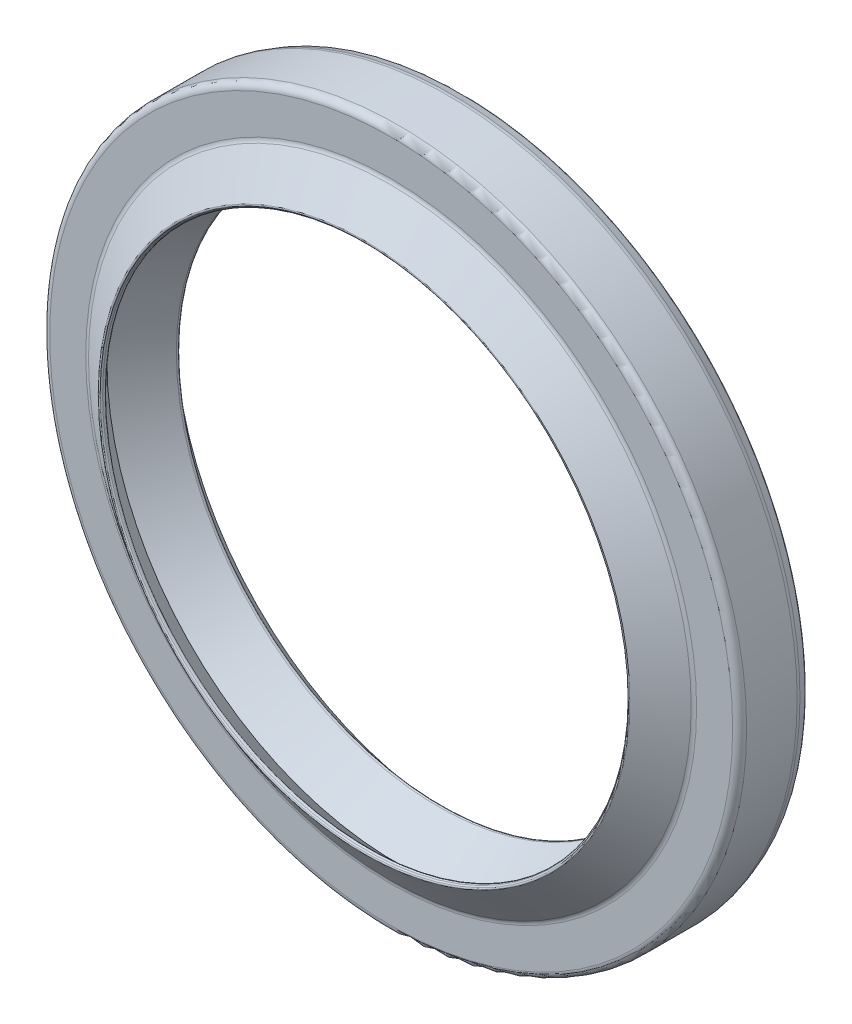
SolidWorks part; units mm, degrees
material "EPDM 60 дюрометр"
ref_plane "Спереди" through (0, 0, 0) normal (0, 0, 1) x (1, 0, 0)
ref_plane "Сверху" through (0, 0, 0) normal (0, 1, 0) x (1, 0, 0)
ref_plane "Справа" through (0, 0, 0) normal (1, 0, 0) x (0, 0, -1)
sketch "Эскиз1" plane through (0, 0, 0) normal (1, 0, 0) x (0, 0, -1)
  line L0 (0, 0) -> (-10, 0) construction
  line L1 (-14, 0) -> (-14, 50) construction
  line L2 (0, 0) -> (0, 37.5) construction
  line L3 (-13.7066, 37.7066) -> (-14, 38)
  line L4 (-14, 38) -> (-10, 43.5)
  line L5 (-10, 43.5) -> (-10, 50)
  line L6 (-10, 50) -> (-1.5, 50)
  line L7 (-1.5, 50) -> (0, 49.5)
  line L8 (0, 49.5) -> (0, 46.5)
  line L9 (0, 46.5) -> (-7, 46.5)
  line L10 (-7, 46.5) -> (-7, 42.5)
  line L11 (-7, 42.5) -> (-1.75, 42.5)
  line L12 (0, 46.5) -> (0, 41.5) construction
  line L13 (-13.288, 37.7011) -> (-9.2839, 41.5)
  line L14 (-9.2839, 41.5) -> (-3.1996, 37.624)
  line L15 (-0.25, 42.5) -> (-0.25, 40.7035)
  line L16 (-0.25, 40.7035) -> (-2.8095, 37.6831)
  line L17 (0, 37.5) -> (-16.6622, 37.5) construction
  arc A0 (-1.75, 42.5) -> (-0.25, 42.5) centre (-1, 42.5) ccw
  arc A1 (-3.1996, 37.624) -> (-2.8095, 37.6831) centre (-3.0384, 37.877) ccw
  arc A2 (-13.7066, 37.7066) -> (-13.288, 37.7011) centre (-13.4945, 37.9188) ccw
  point P3 (-14, 0)
  point P4 (-13.5, 37.5)
  point P8 (0, 49.5)
  point P10 (-14, 38)
  point P11 (-1.5, 50)
  point P12 (-10, 43.5)
  point P33 (-13.5, 37.5)
  dimension "D15" = 1.5
  dimension "D17" = 0.3
  dimension "D1" = 10
  dimension "D2" = 14
  dimension "D3" = 37.5
  dimension "D4" = 50
  dimension "D5" = 1
  dimension "D6" = 0.5
  dimension "D7" = 12.5
  dimension "D8" = 0.5
  dimension "D9" = 1.5
  dimension "D10" = 6
  dimension "D11" = 3
  dimension "D12" = 7
  dimension "D13" = 4
  dimension "D14" = 6
  dimension "D16" = 5
sketch "Эскиз2" plane through (0, 0, 0) normal (1, 0, 0) x (0, 0, -1)
  line L0 (97.746, 203.2468) -> (1097.746, 203.2468) construction
revolve "Повернуть1" add sketch "Эскиз1" angle 360 about L0
fillet "Скругление1" radius 1 1 edges at (-43.5, 0, 10)
fillet "Скругление2" radius 0.2 1 edges at (-38, 0, 14)
fillet "Скругление3" radius 1 1 edges at (-50, 0, 10)
fillet "Скругление4" radius 0.3 1 edges at (-49.5, 0, 0)
fillet "Скругление5" radius 1.5 1 edges at (-50, 0, 1.5)
fillet "Скругление6" radius 0.3 1 edges at (-46.5, 0, 0)
fillet "Скругление7" radius 0.5 1 edges at (-46.5, 0, 7)
fillet "Скругление8" radius 0.3 1 edges at (-42.5, 0, 7)
sketch "Эскиз5" plane through (0, 0, 0) normal (1, 0, 0) x (0, 0, -1)
  line L0 (0, 0) -> (9.7597, 0) construction
  circle A0 centre (-1, 42.5) radius 0.75
revolve "Повернуть2" add sketch "Эскиз5" angle 360 about L0
